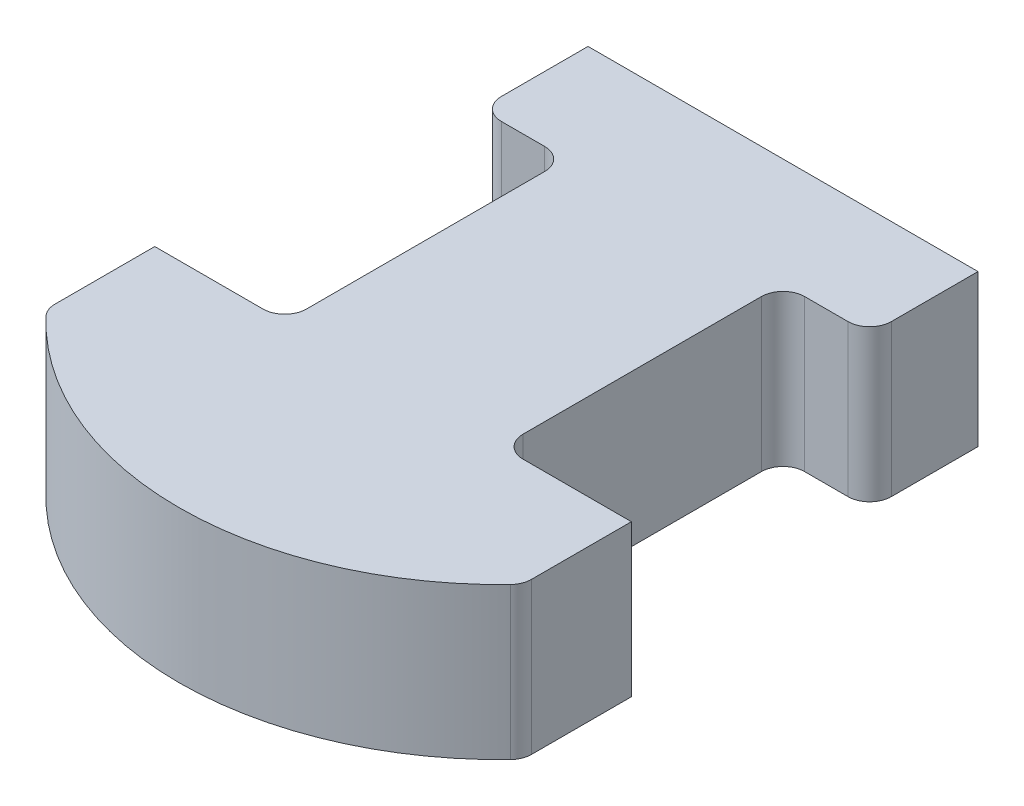
SolidWorks part; units mm, degrees
ref_plane "Front Plane" through (0, 0, 0) normal (0, 0, 1) x (1, 0, 0)
ref_plane "Top Plane" through (0, 0, 0) normal (0, 1, 0) x (1, 0, 0)
ref_plane "Right Plane" through (0, 0, 0) normal (1, 0, 0) x (0, 0, -1)
sketch "Sketch1" plane through (0, 0, 0) normal (0, 1, 0) x (1, 0, 0)
  line L0 (0, 36.6813) -> (0, 17.966) construction
  line L1 (-90, 17.966) -> (90, 17.966)
  line L2 (90, 17.966) -> (90, -32.034)
  line L3 (90, -32.034) -> (50, -32.034)
  line L4 (50, -32.034) -> (50, -162.034)
  line L5 (50, -162.034) -> (110, -162.034)
  line L6 (110, -162.034) -> (110, -212.034)
  line L8 (-110, -162.034) -> (-110, -212.034)
  line L9 (-50, -162.034) -> (-110, -162.034)
  line L10 (-50, -32.034) -> (-50, -162.034)
  line L11 (-90, -32.034) -> (-50, -32.034)
  line L12 (-90, 17.966) -> (-90, -32.034)
  line L13 (0, -260.8089) -> (0, -348.0118) construction
  line L14 (-80, 14.966) -> (80, 14.966)
  line L15 (80, 14.966) -> (80, -29.034)
  line L16 (80, -29.034) -> (45, -29.034)
  line L17 (45, -29.034) -> (45, -167.034)
  line L22 (-95, -167.034) -> (-45, -167.034)
  line L23 (-45, -167.034) -> (-45, -29.034)
  line L24 (-45, -29.034) -> (-80, -29.034)
  line L25 (-80, -29.034) -> (-80, 14.966)
  line L37 (-78.8705, -211.2417) -> (-78.8705, -243.057) construction
  line L38 (-95, -167.034) -> (-95, -211.2417)
  line L39 (0, -229.2418) -> (51.3036, -229.2418) construction
  line L42 (-95, -211.2417) -> (-78.8705, -211.2417)
  line L45 (45, -167.034) -> (95, -167.034)
  line L46 (95, -167.034) -> (95, -211.2417)
  line L47 (95, -211.2417) -> (58.7756, -211.2417)
  arc A0 (-110, -212.034) -> (110, -212.034) centre (0, -112.3821) ccw
  arc A2 (-78.8705, -211.2417) -> (58.7756, -211.2417) centre (-10.0474, -110.7241) ccw
  point P12 (0, -207.8204)
  point P17 (0, 17.966)
  point P31 (-90, -7.034)
  dimension "D7" = 3
  dimension "D1" = 90
  dimension "D2" = 50
  dimension "D3" = 40
  dimension "D4" = 130
  dimension "D5" = 60
  dimension "D6" = 50
  dimension "D8" = 10
  dimension "D9" = 10
  dimension "D10" = 3
  dimension "D11" = 3
  dimension "D12" = 5
  dimension "D13" = 5
  dimension "D14" = 5
  dimension "D16" = 90
  dimension "D17" = 50
extrude "Boss-Extrude1" add sketch "Sketch1" along normal blind 70
sketch "Sketch10" plane through (0, 0, 0) normal (0, 1, 0) x (1, 0, 0)
  line L11 (90, -32.034) -> (90, 17.966)
  line L12 (90, 17.966) -> (-90, 17.966)
  line L13 (-90, 17.966) -> (-90, -32.034)
  line L14 (-90, -32.034) -> (-50, -32.034)
  line L15 (-50, -32.034) -> (-50, -162.034)
  line L16 (-50, -162.034) -> (-110, -162.034)
  line L17 (-110, -162.034) -> (-110, -212.034)
  line L18 (110, -212.034) -> (110, -162.034)
  line L19 (110, -162.034) -> (50, -162.034)
  line L20 (50, -162.034) -> (50, -32.034)
  line L21 (50, -32.034) -> (90, -32.034)
  line L22 (90, -32.034) -> (90, 17.966)
  line L23 (90, 17.966) -> (-90, 17.966)
  line L24 (-90, 17.966) -> (-90, -32.034)
  line L25 (-90, -32.034) -> (-50, -32.034)
  line L26 (-50, -32.034) -> (-50, -162.034)
  line L27 (-50, -162.034) -> (-110, -162.034)
  line L28 (-110, -162.034) -> (-110, -212.034)
  line L29 (110, -212.034) -> (110, -162.034)
  line L30 (110, -162.034) -> (50, -162.034)
  line L31 (50, -162.034) -> (50, -32.034)
  line L32 (50, -32.034) -> (90, -32.034)
  arc A1 (-110, -212.034) -> (110, -212.034) centre (0, -112.3821) ccw
  arc A2 (-110, -212.034) -> (110, -212.034) centre (0, -112.3821) ccw
  dimension "D1" = 0
fillet "Fillet3" radius 10 1 edges at (-90, 35, 32.034)
sketch "Sketch8" plane through (0, 0, 0) normal (0, 1, 0) x (1, 0, 0)
  line L11 (-90, 17.966) -> (-90, -22.034)
  line L12 (-80, -32.034) -> (-50, -32.034)
  line L13 (-50, -32.034) -> (-50, -162.034)
  line L14 (-50, -162.034) -> (-110, -162.034)
  line L15 (-110, -162.034) -> (-110, -212.034)
  line L16 (110, -212.034) -> (110, -162.034)
  line L17 (110, -162.034) -> (50, -162.034)
  line L18 (50, -162.034) -> (50, -32.034)
  line L19 (50, -32.034) -> (90, -32.034)
  line L20 (90, -32.034) -> (90, 17.966)
  line L21 (90, 17.966) -> (-90, 17.966)
  line L22 (-90, 17.966) -> (-90, -22.034)
  line L23 (-80, -32.034) -> (-50, -32.034)
  line L24 (-50, -32.034) -> (-50, -162.034)
  line L25 (-50, -162.034) -> (-110, -162.034)
  line L26 (-110, -162.034) -> (-110, -212.034)
  line L27 (110, -212.034) -> (110, -162.034)
  line L28 (110, -162.034) -> (50, -162.034)
  line L29 (50, -162.034) -> (50, -32.034)
  line L30 (50, -32.034) -> (90, -32.034)
  line L31 (90, -32.034) -> (90, 17.966)
  line L32 (90, 17.966) -> (-90, 17.966)
  arc A7 (-90, -22.034) -> (-80, -32.034) centre (-80, -22.034) ccw
  arc A10 (-110, -212.034) -> (110, -212.034) centre (0, -112.3821) ccw
  arc A14 (-90, -22.034) -> (-80, -32.034) centre (-80, -22.034) ccw
  arc A17 (-110, -212.034) -> (110, -212.034) centre (0, -112.3821) ccw
  dimension "D1" = 0
sketch "Sketch9" plane through (0, 70, 0) normal (0, 1, 0) x (1, 0, 0)
  line L11 (-90, 17.966) -> (-90, -22.034)
  line L12 (-80, -32.034) -> (-50, -32.034)
  line L13 (-50, -32.034) -> (-50, -162.034)
  line L14 (-50, -162.034) -> (-110, -162.034)
  line L15 (-110, -162.034) -> (-110, -212.034)
  line L16 (110, -212.034) -> (110, -162.034)
  line L17 (110, -162.034) -> (50, -162.034)
  line L18 (50, -162.034) -> (50, -32.034)
  line L19 (50, -32.034) -> (90, -32.034)
  line L20 (90, -32.034) -> (90, 17.966)
  line L21 (90, 17.966) -> (-90, 17.966)
  line L22 (-90, 17.966) -> (-90, -22.034)
  line L23 (-80, -32.034) -> (-50, -32.034)
  line L24 (-50, -32.034) -> (-50, -162.034)
  line L25 (-50, -162.034) -> (-110, -162.034)
  line L26 (-110, -162.034) -> (-110, -212.034)
  line L27 (110, -212.034) -> (110, -162.034)
  line L28 (110, -162.034) -> (50, -162.034)
  line L29 (50, -162.034) -> (50, -32.034)
  line L30 (50, -32.034) -> (90, -32.034)
  line L31 (90, -32.034) -> (90, 17.966)
  line L32 (90, 17.966) -> (-90, 17.966)
  arc A7 (-90, -22.034) -> (-80, -32.034) centre (-80, -22.034) ccw
  arc A10 (-110, -212.034) -> (110, -212.034) centre (0, -112.3821) ccw
  arc A14 (-90, -22.034) -> (-80, -32.034) centre (-80, -22.034) ccw
  arc A17 (-110, -212.034) -> (110, -212.034) centre (0, -112.3821) ccw
  dimension "D1" = 0
extrude "Boss-Extrude2" add sketch "Sketch9" against normal blind 10
fillet "Fillet4" radius 10 13 edges at (-80, 30, 29.034) (80, 30, 29.034) (-45, 30, 29.034) (45, 30, 29.034) (45, 30, 167.034) (-45, 30, 167.034) (-50, 35, 162.034) (50, 35, 32.034) (50, 35, 162.034) (-50, 35, 32.034) (-110, 35, 212.034) (110, 35, 212.034) (90, 35, 32.034)
